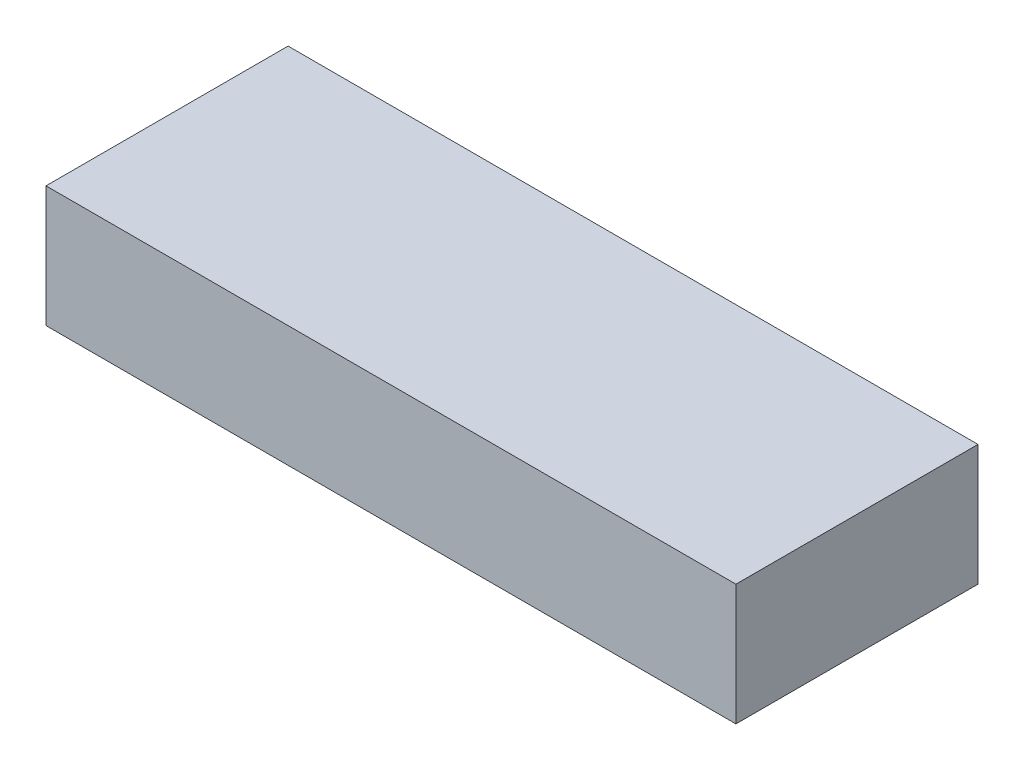
SolidWorks part; units mm, degrees
ref_plane "Front Plane" through (0, 0, 0) normal (0, 0, 1) x (1, 0, 0)
ref_plane "Top Plane" through (0, 0, 0) normal (0, 1, 0) x (1, 0, 0)
ref_plane "Right Plane" through (0, 0, 0) normal (1, 0, 0) x (0, 0, -1)
sketch "Sketch1" plane through (0, 0, 0) normal (0, 1, 0) x (1, 0, 0)
  line L1 (0, 0) -> (57, 0)
  line L2 (0, 0) -> (0, 20)
  line L3 (0, 20) -> (57, 20)
  line L4 (57, 0) -> (57, 20)
extrude "Boss-Extrude1" add sketch "Sketch1" against normal blind 10
